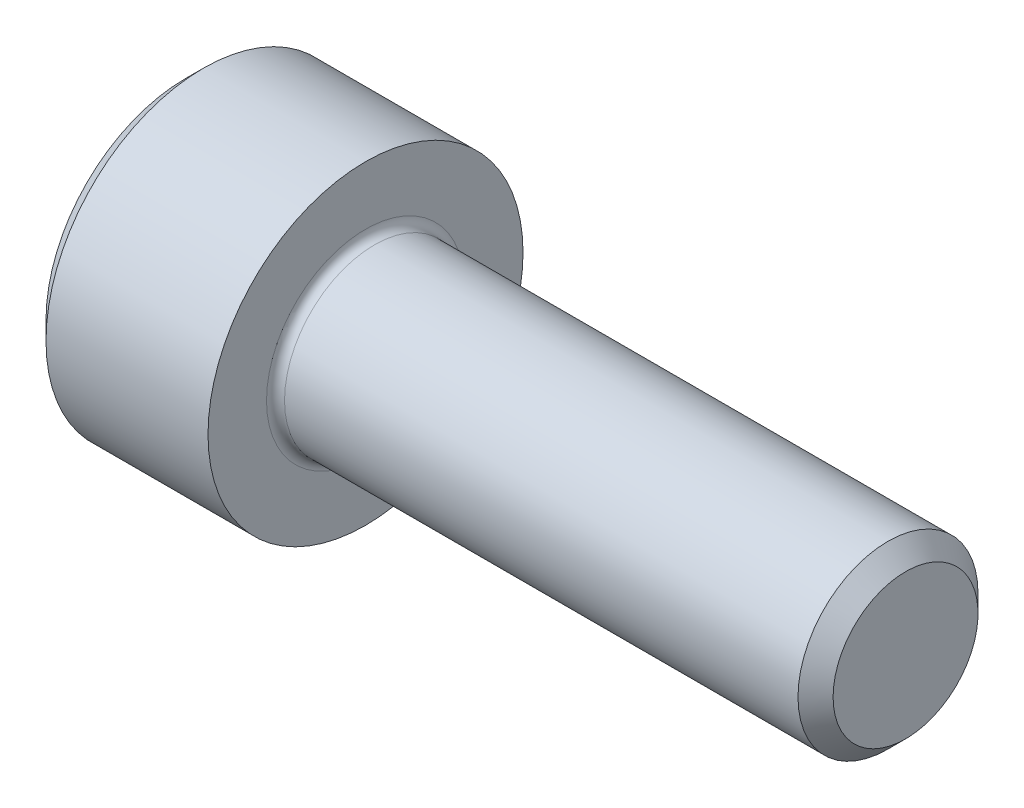
SolidWorks part; units mm, degrees
revolve "Base-Revolve" add sketch "BodySke"
sketch "BodySke" plane through (0, 0, 0) normal (0, 0, 1) x (1, 0, 0)
  line L0 (0, 0) -> (0, 3.1)
  line L1 (0.4, 3.5) -> (4, 3.5)
  line L2 (4, 3.5) -> (4, 2)
  line L3 (4, 2) -> (15.61, 2)
  line L4 (16, 1.61) -> (16, 0)
  line L5 (16, 0) -> (0, 0)
  line L6 (-31.75, 0) -> (127, 0) construction
  line L7 (0, 3.1) -> (0.4, 3.5)
  line L8 (16, 1.61) -> (15.61, 2)
  line L9 (0, -3.1) -> (0.4, -3.5) construction
  line L10 (16, -1.61) -> (15.61, -2) construction
  line L11 (4.7, 9.525) -> (4.7, 3.175) construction
  line L12 (4, 9.525) -> (4, 3.175) construction
  line L13 (-34, 9.525) -> (-34, 3.175) construction
  dimension "Diameter" = 4
  dimension "Head_ht" = 4
  dimension "Length" = 12
  dimension "Body_ch_ang" = 45
  dimension "Head_dia" = 7
  dimension "Head_ch_ang" = 45
  dimension "Minor_dia" = 3.22
  dimension "Advance" = 0.7
  dimension "Thread_nom" = 12
  dimension "Thread_length" = 50
  dimension "Head_ch_ht" = 0.4
cosmetic thread "ThreadCosmetic" [suppressed]
fillet "Fillet1" radius 0.2 1 edges at (4, 0, 2)
ref_plane "Plane1" through (0, 0, 0) normal (0, 0, 1) x (1, 0, 0)
ref_plane "Plane2" through (0, 0, 0) normal (0, 1, 0) x (1, 0, 0)
ref_plane "Plane3" through (0, 0, 0) normal (1, 0, 0) x (0, 0, -1)
sketch "Sketch2" plane through (0, 0, 0) normal (0, 0, 1) x (1, 0, 0)
  line L0 (0, 1.5355) -> (2, 1.5355)
  line L1 (2, 1.5355) -> (2.8865, 0)
  line L2 (-31.75, 0) -> (127, 0) construction
  line L3 (2.8865, 0) -> (0, 0)
  line L4 (0, 0) -> (0, 1.5355)
  line L5 (0, 3.1) -> (0, -3.1) construction
  line L6 (0, 0) -> (47.625, 0) construction
  line L7 (4, -3.5) -> (4, 3.5) construction
  dimension "D1" = 1.5355
  dimension "D2" = 60
revolve "Hex-PreBroach" cut sketch "Sketch2" angle 360 about L6
sketch "Sketch3" plane through (0, 0, 0) normal (-1, 0, 0) x (0, 0.5, 0.866)
  line L0 (0.8865, 1.5355) -> (-0.8865, 1.5355)
  line L1 (-0.8865, 1.5355) -> (-1.773, 0)
  line L2 (0.8865, 1.5355) -> (1.773, 0)
  line L3 (0.8865, -1.5355) -> (1.773, 0)
  line L4 (0.8865, -1.5355) -> (-0.8865, -1.5355)
  line L5 (-0.8865, -1.5355) -> (-1.773, 0)
  dimension "D1" = 1.5355
  dimension "D2" = 1.5355
  dimension "Hex_size" = 3.071
extrude "Hex" cut sketch "Sketch3" against normal blind 2
sketch "Sketch4" plane through (0, 0, 0) normal (-1, 0, 0) x (0, 0, 1)
  line L0 (0, 0) -> (1.7399, 0)
  line L1 (0, 0) -> (6.1484, 3.5498) construction
  line L2 (0, 0) -> (0.8699, 1.5068)
  line L3 (1.4457, 0.3947) -> (1.6607, 0.5189)
  line L4 (1.0647, 1.0546) -> (1.2797, 1.1788)
  arc A0 (1.4457, 0.3947) -> (1.0647, 1.0546) centre (0, 0) ccw
  arc A1 (1.7399, 0) -> (1.6607, 0.5189) centre (0, 0) ccw
  arc A2 (0.8699, 1.5068) -> (1.2797, 1.1788) centre (0, 0) cw
  dimension "D1" = 30
  dimension "D2" = 60
  dimension "Spline_p_dim" = 0.762
  dimension "D3" = 0.381
extrude "Spline" [suppressed] cut sketch "Sketch4" against normal blind 2
pattern_circular "CirPattern1" [suppressed] count 6 every 60
sketch "Sketch5" plane through (0, 0, 0) normal (0, 0, 1) x (1, 0, 0)
  line L0 (-31.75, 0) -> (127, 0) construction
  line L2 (0, 3.1) -> (0, -3.1) construction
  circle A0 centre (1.6, 0) radius 0.675
  dimension "Drilled_hole_dia" = 1.35
  dimension "Drilled_hole_loc" = 1.6
extrude "Hole" [suppressed] cut sketch "Sketch5" against normal through all and the other way through all
pattern_circular "Drilled-4" [suppressed] count 2 every 60
pattern_circular "Drilled-6" [suppressed] count 3 every 60
sketch "ThdSchSke" plane through (0, 0, 0) normal (0, 0, 1) x (1, 0, 0)
  line L0 (4.7, -1.61) -> (4.4269, -2)
  line L1 (4.7, -1.61) -> (4.9731, -2)
  line L2 (4.9731, -2) -> (4.9731, -2.5)
  line L3 (-3.175, 0) -> (5.1513, 0) construction
  line L5 (4.9731, -2.5) -> (4.4269, -2.5)
  line L6 (4.4269, -2.5) -> (4.4269, -2)
  line L7 (0, 3.1) -> (0, -3.1) construction
  dimension "Thread_minor" = 3.22
  dimension "Diameter" = 4
  dimension "Start" = 4.7
revolve "ThreadSchematic" [suppressed] cut sketch "ThdSchSke" angle 360 about L3
pattern_linear "ThdSchPat" [suppressed]
equation "\"D2@Sketch3\" = \"Hex_size@Sketch3\" / 2"
equation "\"D1@Sketch3\" = \"Hex_size@Sketch3\" / 2"
equation "\"D1@Sketch2\" = \"Hex_size@Sketch3\" / 2"
equation "\"D3@Sketch4\" = \"Spline_p_dim@Sketch4\" / 2"
equation "\"Thread_minor@ThreadCosmetic\"  =  \"Minor_dia@BodySke\""
equation "\"D2@CirPattern1\" = 360 / \"Num_teeth@CirPattern1\""
equation "\"Wall_thickness@Sketch2\" = \"Head_ht@BodySke\" - \"Key_eng@Hex\""
equation "\"Thread_length@ThreadCosmetic\" = ((sgn( (\"Length@BodySke\" - \"Advance@BodySke\" ) - \"Thread_nom@BodySke\" )-1)*( (\"Length@BodySke\" - \"Advance@BodySke\" ) - \"Thread_nom@BodySke\" ))/-2+ \"Thread_nom@BodySke\""
equation "\"Thread_minor@ThdSchSke\" = \"Minor_dia@BodySke\""
equation "\"Diameter@ThdSchSke\" = \"Diameter@BodySke\""
equation "\"Overcut@ThdSchSke\" = \"Diameter@BodySke\" * 1.25"
equation "\"Start@ThdSchSke\" = \"Head_ht@BodySke\" + \"Length@BodySke\" - \"Thread_length@ThreadCosmetic\"  '---Non-countersunk---"
equation "\"Num_threads@ThdSchPat\" = int( \"Thread_length@ThreadCosmetic\" / \"Advance@BodySke\" + 0.999 )  + 1"
equation "\"Advance@ThdSchPat\" = \"Thread_length@ThreadCosmetic\" /  (\"Num_threads@ThdSchPat\" - 1) 'relax it"
equation "\"Num_threads@ThdSchPat\" = \"Num_threads@ThdSchPat\" - sgn( \"Num_threads@ThdSchPat\" - 1) '---chamfered tips only---"
